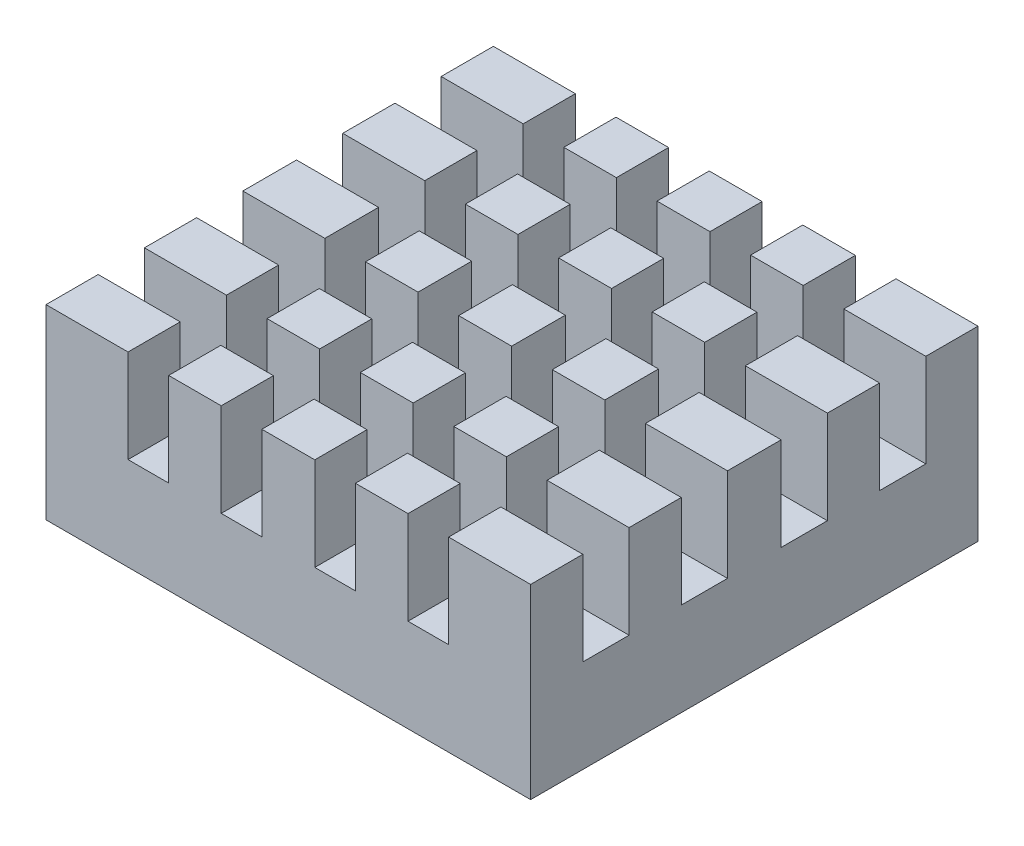
SolidWorks part; units mm, degrees
ref_plane "Front Plane" through (0, 0, 0) normal (0, 0, 1) x (1, 0, 0)
ref_plane "Top Plane" through (0, 0, 0) normal (0, 1, 0) x (1, 0, 0)
ref_plane "Right Plane" through (0, 0, 0) normal (1, 0, 0) x (0, 0, -1)
sketch "Sketch1" plane through (0, 0, 0) normal (0, 1, 0) x (1, 0, 0)
  line L1 (6.5, 6) -> (-6.5, 6)
  line L2 (6.5, 6) -> (6.5, -6)
  line L3 (6.5, -6) -> (-6.5, -6)
  line L4 (-6.5, 6) -> (-6.5, -6)
  line L5 (6.5, 6) -> (-6.5, -6) construction
  line L6 (6.5, -6) -> (-6.5, 6) construction
  point P0 (0, 0)
  dimension "D1" = 12
  dimension "D2" = 13
extrude "Boss-Extrude1" add sketch "Sketch1" along normal blind 5
sketch "Sketch2" plane through (0, 5, 0) normal (0, 1, 0) x (1, 0, 0)
  line L0 (6.5, 6) -> (-6.5, 6) construction
  line L1 (-1.8, 6) -> (-0.71, 6)
  line L2 (-1.8, 6) -> (-1.8, 4.6)
  line L3 (-1.8, -6) -> (-0.71, -6)
  line L4 (-0.71, 6) -> (-0.71, 4.6)
  line L5 (-6.5, -6) -> (6.5, -6) construction
  line L6 (6.5, -6) -> (6.5, 6) construction
  line L7 (3.21, 6) -> (4.3, 6)
  line L8 (3.21, 6) -> (3.21, 4.6)
  line L9 (3.21, -6) -> (4.3, -6)
  line L10 (4.3, 6) -> (4.3, 4.6)
  line L11 (0.71, 6) -> (1.8, 6)
  line L12 (0.71, 6) -> (0.71, 4.6)
  line L13 (0.71, -6) -> (1.8, -6)
  line L14 (1.8, 6) -> (1.8, 4.6)
  line L15 (0, 6) -> (0, -6) construction
  line L16 (6.5, 0) -> (-6.5, 0) construction
  line L17 (-4.3, -4.6) -> (-4.3, -6)
  line L18 (-4.3, -3.36) -> (-6.5, -3.36)
  line L19 (6.5, -4.6) -> (4.3, -4.6)
  line L20 (6.5, -4.6) -> (6.5, -3.36)
  line L21 (6.5, -3.36) -> (4.3, -3.36)
  line L22 (-6.5, -4.6) -> (-6.5, -3.36)
  line L23 (-6.5, 6) -> (-6.5, -6) construction
  line L24 (-6.5, -1.96) -> (-4.3, -1.96)
  line L25 (-6.5, -1.96) -> (-6.5, -0.72)
  line L26 (-6.5, -0.72) -> (-4.3, -0.72)
  line L27 (6.5, -1.96) -> (6.5, -0.72)
  line L28 (-3.21, -4.6) -> (-3.21, -6)
  line L29 (-6.5, 1.96) -> (-4.3, 1.96)
  line L30 (-6.5, 1.96) -> (-6.5, 0.72)
  line L31 (-6.5, 0.72) -> (-4.3, 0.72)
  line L32 (6.5, 1.96) -> (6.5, 0.72)
  line L33 (6.5, 4.6) -> (4.3, 4.6)
  line L34 (6.5, 4.6) -> (6.5, 3.36)
  line L35 (6.5, 3.36) -> (4.3, 3.36)
  line L36 (-6.5, 4.6) -> (-6.5, 3.36)
  line L37 (-4.3, 6) -> (-3.21, 6)
  line L38 (-4.3, 6) -> (-4.3, 4.6)
  line L39 (-4.3, -6) -> (-3.21, -6)
  line L40 (-3.21, 6) -> (-3.21, 4.6)
  line L41 (-4.3, -4.6) -> (-6.5, -4.6)
  line L42 (-3.21, -1.96) -> (-1.8, -1.96)
  line L43 (-3.21, -0.72) -> (-1.8, -0.72)
  line L44 (-3.21, 0.72) -> (-1.8, 0.72)
  line L45 (-3.21, 1.96) -> (-1.8, 1.96)
  line L46 (-4.3, 4.6) -> (-6.5, 4.6)
  line L47 (-4.3, 3.36) -> (-6.5, 3.36)
  line L48 (-4.3, 3.36) -> (-4.3, 1.96)
  line L49 (-3.21, 3.36) -> (-3.21, 1.96)
  line L50 (-4.3, 0.72) -> (-4.3, -0.72)
  line L51 (-3.21, 0.72) -> (-3.21, -0.72)
  line L52 (-4.3, -1.96) -> (-4.3, -3.36)
  line L53 (-3.21, -1.96) -> (-3.21, -3.36)
  line L54 (-1.8, -4.6) -> (-1.8, -6)
  line L55 (-0.71, -4.6) -> (-0.71, -6)
  line L56 (0.71, -4.6) -> (0.71, -6)
  line L57 (1.8, -4.6) -> (1.8, -6)
  line L58 (3.21, -4.6) -> (3.21, -6)
  line L59 (4.3, -4.6) -> (4.3, -6)
  line L60 (-1.8, -4.6) -> (-3.21, -4.6)
  line L61 (0.71, -4.6) -> (-0.71, -4.6)
  line L62 (3.21, -4.6) -> (1.8, -4.6)
  line L63 (3.21, -3.36) -> (1.8, -3.36)
  line L64 (0.71, -3.36) -> (-0.71, -3.36)
  line L65 (-1.8, -3.36) -> (-3.21, -3.36)
  line L66 (-0.71, -1.96) -> (0.71, -1.96)
  line L67 (-0.71, -0.72) -> (0.71, -0.72)
  line L68 (-0.71, 0.72) -> (0.71, 0.72)
  line L69 (-0.71, 1.96) -> (0.71, 1.96)
  line L70 (-1.8, 3.36) -> (-3.21, 3.36)
  line L71 (-1.8, 4.6) -> (-3.21, 4.6)
  line L72 (0.71, 4.6) -> (-0.71, 4.6)
  line L73 (0.71, 3.36) -> (-0.71, 3.36)
  line L74 (1.8, 1.96) -> (3.21, 1.96)
  line L75 (1.8, 0.72) -> (3.21, 0.72)
  line L76 (1.8, -0.72) -> (3.21, -0.72)
  line L77 (1.8, -1.96) -> (3.21, -1.96)
  line L78 (4.3, -1.96) -> (6.5, -1.96)
  line L79 (4.3, -0.72) -> (6.5, -0.72)
  line L80 (4.3, 0.72) -> (6.5, 0.72)
  line L81 (4.3, 1.96) -> (6.5, 1.96)
  line L82 (3.21, 3.36) -> (1.8, 3.36)
  line L83 (3.21, 4.6) -> (1.8, 4.6)
  line L84 (4.3, 3.36) -> (4.3, 1.96)
  line L85 (3.21, 3.36) -> (3.21, 1.96)
  line L86 (1.8, 3.36) -> (1.8, 1.96)
  line L87 (0.71, 3.36) -> (0.71, 1.96)
  line L88 (-0.71, 3.36) -> (-0.71, 1.96)
  line L89 (-1.8, 3.36) -> (-1.8, 1.96)
  line L90 (-1.8, 0.72) -> (-1.8, -0.72)
  line L91 (-0.71, 0.72) -> (-0.71, -0.72)
  line L92 (0.71, 0.72) -> (0.71, -0.72)
  line L93 (1.8, 0.72) -> (1.8, -0.72)
  line L94 (3.21, 0.72) -> (3.21, -0.72)
  line L95 (4.3, 0.72) -> (4.3, -0.72)
  line L96 (4.3, -1.96) -> (4.3, -3.36)
  line L97 (3.21, -1.96) -> (3.21, -3.36)
  line L98 (1.8, -1.96) -> (1.8, -3.36)
  line L99 (0.71, -1.96) -> (0.71, -3.36)
  line L100 (-0.71, -1.96) -> (-0.71, -3.36)
  line L101 (-1.8, -1.96) -> (-1.8, -3.36)
  dimension "D1" = 1.24
  dimension "D2" = 1.09
  dimension "D3" = 2.2
  dimension "D4" = 1.41
  dimension "D5" = 1.42
  dimension "D6" = 1.4
  dimension "D7" = 1.4
  dimension "D8" = 1.44
extrude "Cut-Extrude1" cut sketch "Sketch2" against normal blind 2.5
